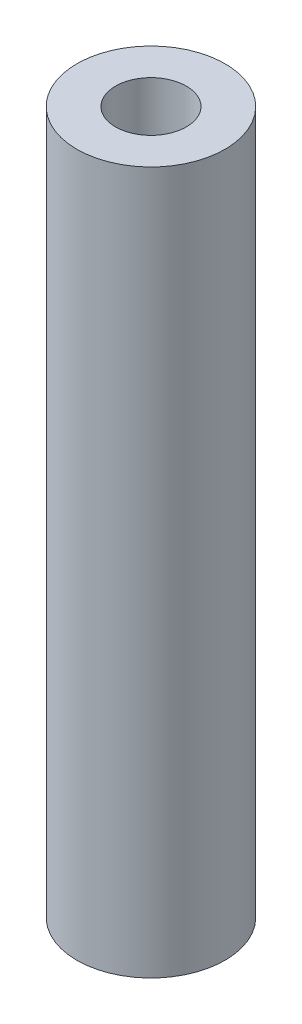
SolidWorks part; units mm, degrees
ref_plane "Front Plane" through (0, 0, 0) normal (0, 0, 1) x (1, 0, 0)
ref_plane "Top Plane" through (0, 0, 0) normal (0, 1, 0) x (1, 0, 0)
ref_plane "Right Plane" through (0, 0, 0) normal (1, 0, 0) x (0, 0, -1)
sketch "Sketch1" plane through (0, 0, 0) normal (0, 1, 0) x (1, 0, 0)
  circle A0 centre (0, 0) radius 4.5
  circle A2 centre (0, 0) radius 2.15
  dimension "D1" = 9
  dimension "D2" = 4.3
extrude "Boss-Extrude1" add sketch "Sketch1" along normal mid plane 42.65
